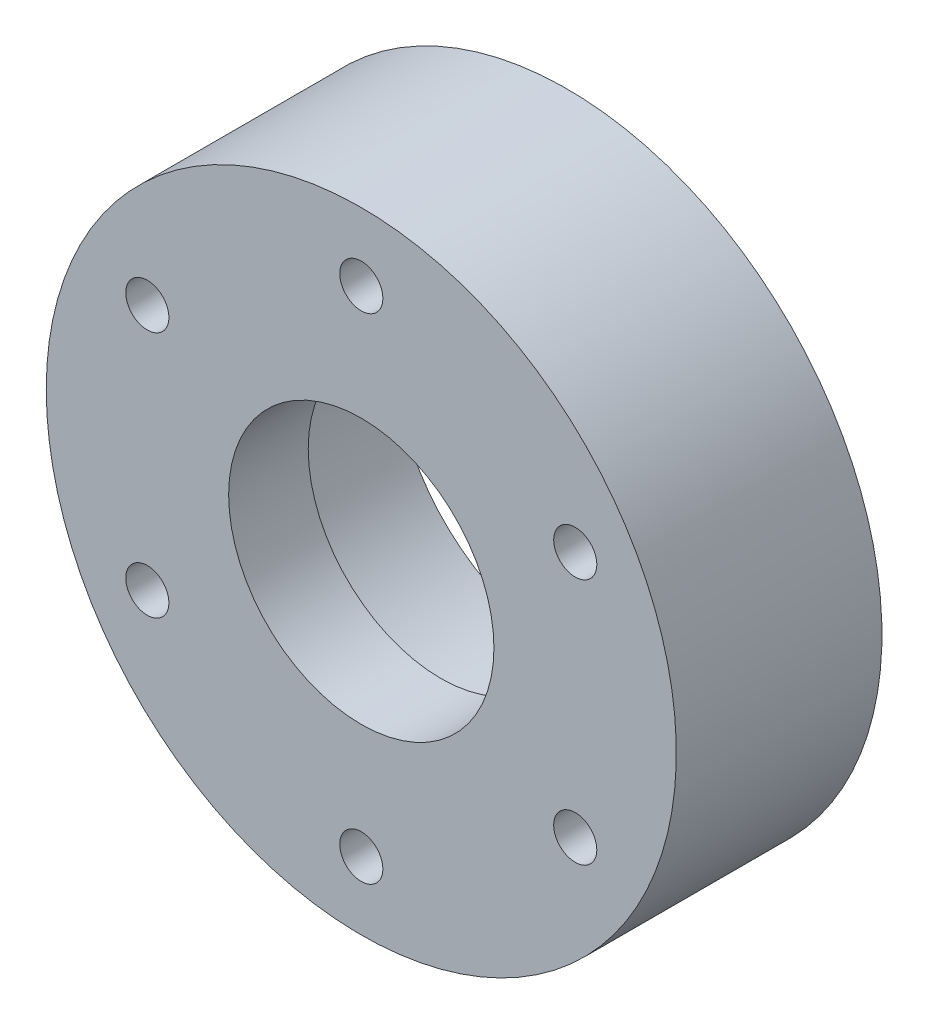
SolidWorks part; units mm, degrees
ref_plane "Front Plane" through (0, 0, 0) normal (0, 0, 1) x (1, 0, 0)
ref_plane "Top Plane" through (0, 0, 0) normal (0, 1, 0) x (1, 0, 0)
ref_plane "Right Plane" through (0, 0, 0) normal (1, 0, 0) x (0, 0, -1)
sketch "Sketch1" plane through (0, 0, 0) normal (1, 0, 0) x (0, 0, -1)
  line L0 (0, 0) -> (-62.4415, 0) construction
  line L1 (-31, 47.5) -> (0, 47.5)
  line L2 (0, 47.5) -> (0, 26)
  line L3 (0, 26) -> (-19, 26)
  line L4 (-19, 26) -> (-19, 20)
  line L5 (-19, 20) -> (-31, 20)
  line L6 (-31, 20) -> (-31, 47.5)
  dimension "D1" = 40
  dimension "D2" = 52
  dimension "D3" = 12
  dimension "D4" = 19
  dimension "D5" = 31
  dimension "D6" = 95
revolve "Revolve1" add sketch "Sketch1" angle 360 about L0
sketch "Sketch2" plane through (0, 0, 31) normal (0, 0, 1) x (1, 0, 0)
  circle A1 centre (0, 37.25) radius 3.25
  circle A2 centre (0, 37.25) radius 3.25
  dimension "D1" = 0
extrude "Cut-Extrude1" cut sketch "Sketch2" against normal through all
pattern_circular "CirPattern1" count 6 over 360 about axis through (0, 0, 0) along (0, 0, 1) of "Cut-Extrude1"
